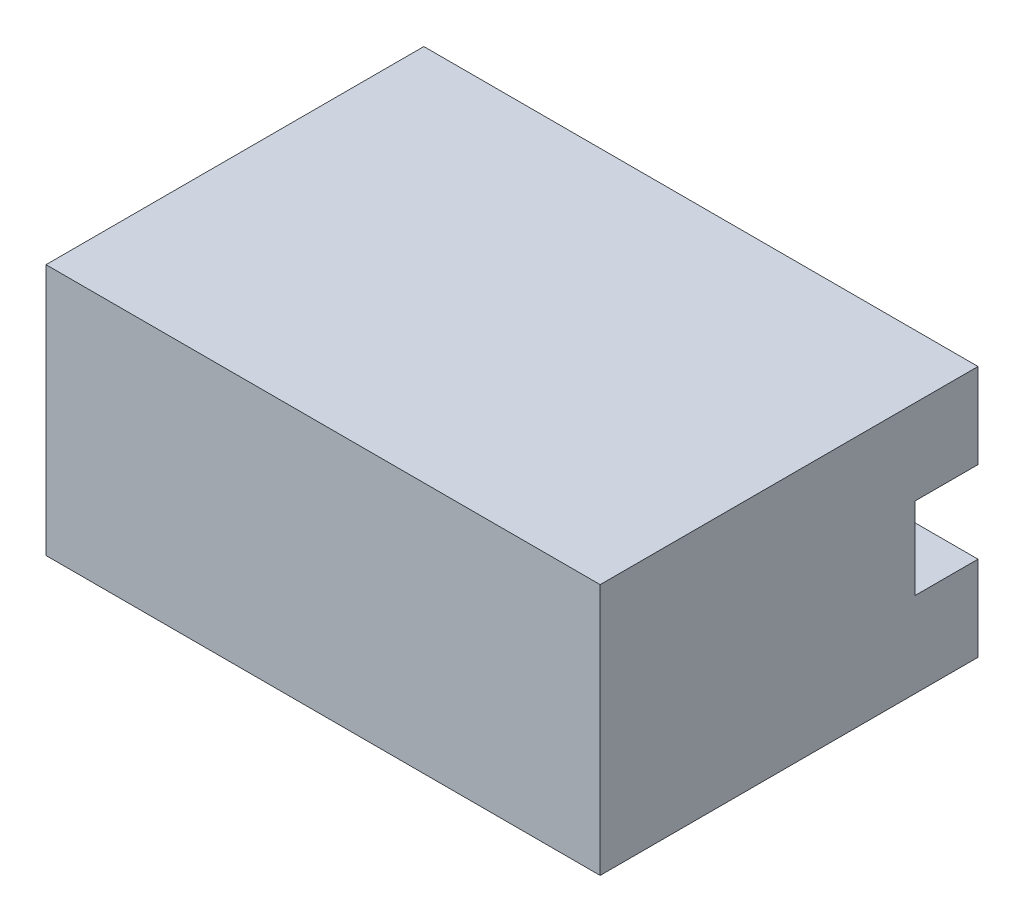
SolidWorks part; units mm, degrees
ref_plane "Front Plane" through (0, 0, 0) normal (0, 0, 1) x (1, 0, 0)
ref_plane "Top Plane" through (0, 0, 0) normal (0, 1, 0) x (1, 0, 0)
ref_plane "Right Plane" through (0, 0, 0) normal (1, 0, 0) x (0, 0, -1)
sketch "Sketch1" plane through (0, 0, 0) normal (0, 0, 1) x (1, 0, 0)
  line L1 (-15, 5) -> (15, 5)
  line L2 (-15, 5) -> (-15, -5)
  line L3 (-15, -5) -> (15, -5)
  line L4 (15, 5) -> (15, -5)
  point P4 (0, 5)
  point P6 (15, 0)
  dimension "D1" = 30
  dimension "D2" = 10
extrude "Boss-Extrude1" add sketch "Sketch1" along normal mid plane 13
sketch "Sketch3" plane through (0, -5, 0) normal (0, -1, 0) x (1, 0, 0)
  line L1 (17, 11) -> (4, 11)
  line L2 (17, 11) -> (17, -11)
  line L3 (17, -11) -> (4, -11)
  line L4 (4, 11) -> (4, -11)
  point P4 (17, 0)
  dimension "D1" = 4
  dimension "D2" = 13
  dimension "D3" = 22
extrude "Cut-Extrude3" cut sketch "Sketch3" against normal through all
sketch "Sketch10" plane through (4, 0, 0) normal (1, 0, 0) x (0, 0, -1)
  line L1 (-6.5, -5) -> (6.5, -5)
  line L2 (-6.5, -5) -> (-6.5, 5)
  line L3 (-6.5, 5) -> (6.5, 5)
  line L4 (6.5, -5) -> (6.5, 5)
  line L5 (-6.5, -5) -> (6.5, 5) construction
  line L6 (-6.5, 5) -> (6.5, -5) construction
  point P0 (0, 0)
extrude "Boss-Extrude3" add sketch "Sketch10" along normal blind 3
sketch "Sketch12" plane through (0, 0, -6.5) normal (0, 0, -1) x (-1, 0, 0)
  line L0 (15, 5) -> (15, -5) construction
  line L1 (-7, -1.625) -> (15, -1.625)
  line L2 (-7, -1.625) -> (-7, 1.625)
  line L3 (-7, 1.625) -> (15, 1.625)
  line L4 (15, -1.625) -> (15, 1.625)
  line L5 (-7, -1.625) -> (15, 1.625) construction
  line L6 (-7, 1.625) -> (15, -1.625) construction
  line L9 (6.6, 0) -> (-6.6, 0) construction
  point P0 (4, 0)
  point P7 (-7, 0)
  dimension "D1" = 3.25
  dimension "D2" = 22
extrude "Cut-Extrude5" cut sketch "Sketch12" against normal blind 0.5
sketch "Sketch15" plane through (0, 0, -6.5) normal (0, 0, -1) x (-1, 0, 0)
  line L1 (-7, 5) -> (15, 5)
  line L2 (-7, 5) -> (-7, 1.625)
  line L3 (-7, 1.625) -> (15, 1.625)
  line L4 (15, 5) -> (15, 1.625)
extrude "Boss-Extrude6" add sketch "Sketch15" along normal blind 2
mirror "Mirror5" about plane through (0, 0, 0) normal (0, 1, 0) of "Boss-Extrude6"
